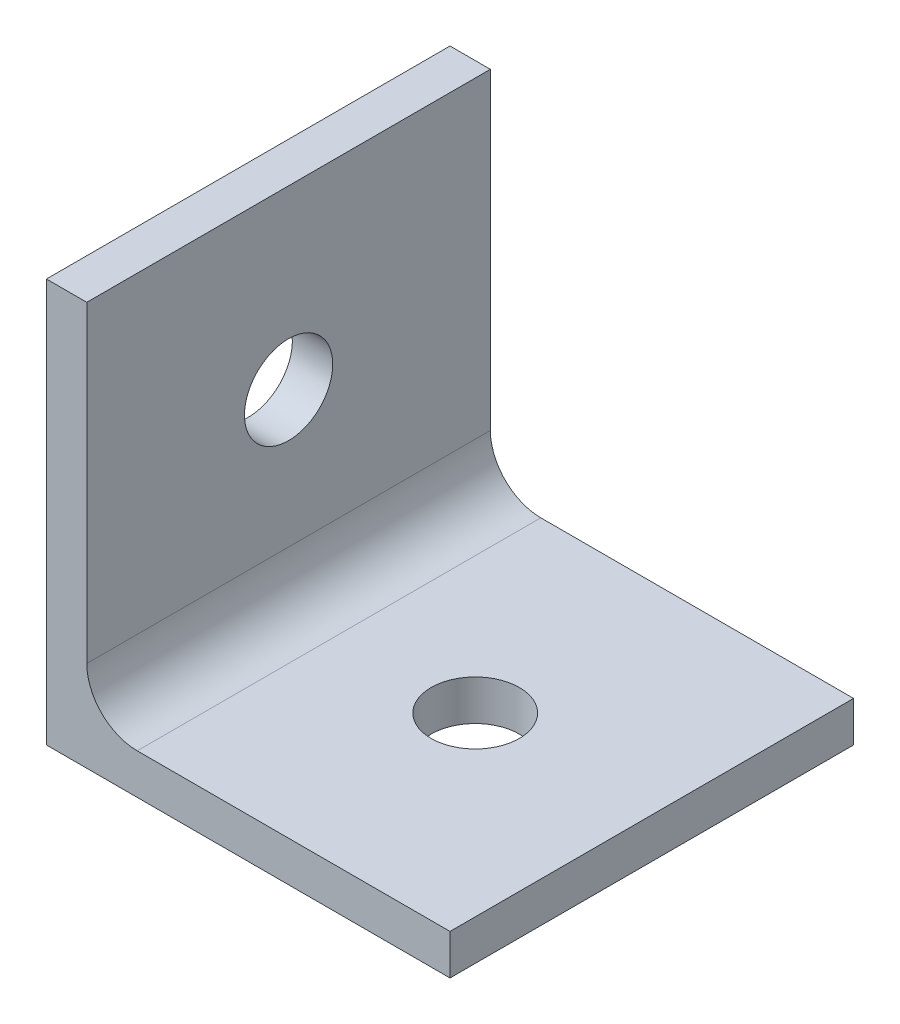
SolidWorks part; units mm, degrees
material "1.0037 (S235JR)"
ref_plane "Ebene vorne" through (0, 0, 0) normal (0, 0, 1) x (1, 0, 0)
ref_plane "Ebene oben" through (0, 0, 0) normal (0, 1, 0) x (1, 0, 0)
ref_plane "Ebene rechts" through (0, 0, 0) normal (1, 0, 0) x (0, 0, -1)
sketch "Skizze1" plane through (0, 0, 0) normal (0, 0, 1) x (1, 0, 0)
  line L0 (0, 0) -> (80, 0)
  line L1 (80, 0) -> (80, 8)
  line L2 (80, 8) -> (18, 8)
  line L3 (8, 18) -> (8, 80)
  line L4 (8, 80) -> (0, 80)
  line L5 (0, 80) -> (0, 0)
  arc A0 (18, 8) -> (8, 18) centre (18, 18) cw
  dimension "D5" = 10
  dimension "D1" = 8
  dimension "D2" = 8
  dimension "D3" = 80
  dimension "D4" = 80
extrude "Aufsatz Auftragen Main Body" add sketch "Skizze1" along normal mid plane 80
sketch "Skizze3" plane through (0, 8, 0) normal (0, 1, 0) x (1, 0, 0)
  line L0 (0, -40) -> (0, 40) construction
  circle A0 centre (45, 0) radius 8.75
  point P4 (0, 0)
  point P5 (0, 0)
  dimension "D1" = 17.5
  dimension "D2" = 45
extrude "Bohrung Horizontal" cut sketch "Skizze3" against normal through all
sketch "Skizze4" plane through (8, 0, 0) normal (1, 0, 0) x (0, 0, -1)
  line L1 (-40, 0) -> (40, 0) construction
  circle A0 centre (0, 45) radius 8.75
  point P2 (0, 0)
  dimension "D1" = 17.5
  dimension "D2" = 45
other "AusrichtungGruppe1"
extrude "Bohrung Vertikal" cut sketch "Skizze4" against normal through all
